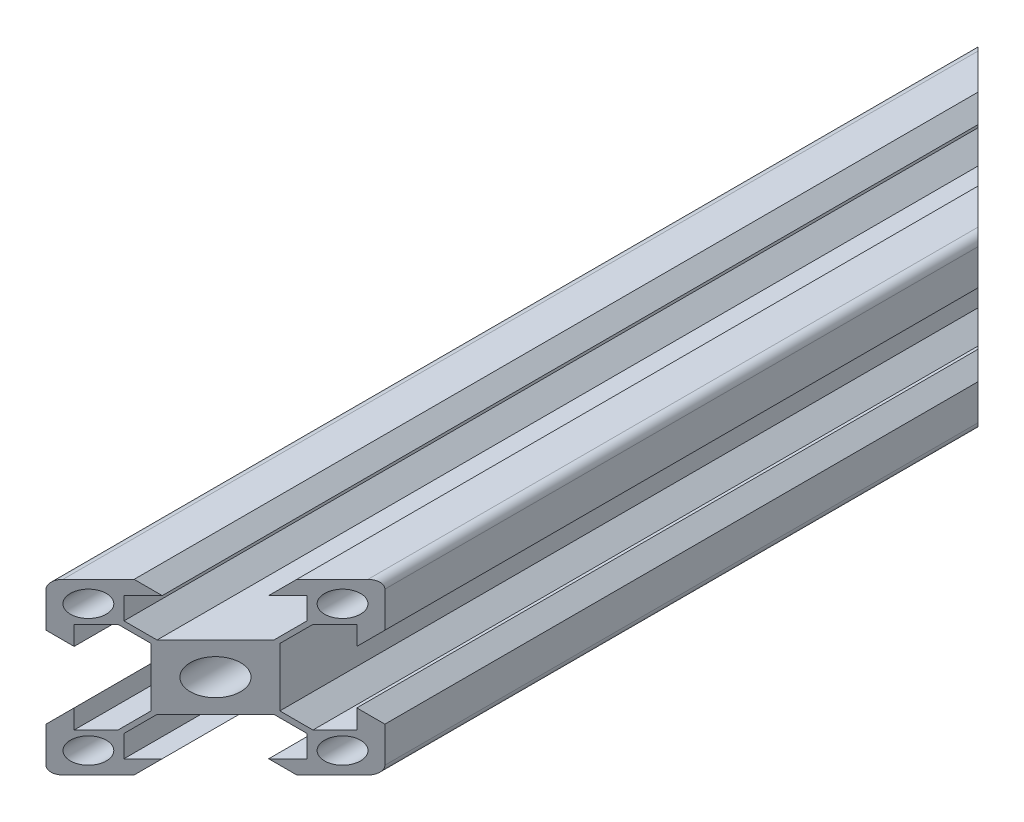
SolidWorks part; units mm, degrees
material "铝管"
ref_plane "前视基准面" through (0, 0, 0) normal (0, 0, 1) x (1, 0, 0)
ref_plane "上视基准面" through (0, 0, 0) normal (0, 1, 0) x (1, 0, 0)
ref_plane "右视基准面" through (0, 0, 0) normal (1, 0, 0) x (0, 0, -1)
sketch "草图1" plane through (0, 0, 0) normal (0, 0, 1) x (1, 0, 0)
  line L0 (0, 0) -> (-40.5659, 40.5659) construction
  line L1 (0, 0) -> (0, 75.5033) construction
  line L2 (-10, 10) -> (-10, 4.8)
  line L3 (-10, 4.8) -> (-8.34, 3.14)
  line L4 (-8.34, 3.14) -> (-8.34, 5.4)
  line L5 (-5.7536, 5.4) -> (-3.8, 3.4464)
  line L6 (-3.8, 3.4464) -> (-3.8, -3.4464)
  line L7 (-3.8, 0) -> (15.6715, 0) construction
  line L8 (-5.4, 8.34) -> (-5.4, 5.7536)
  line L9 (-3.4464, 3.8) -> (3.4464, 3.8)
  line L10 (-5.4, 5.7536) -> (-3.4464, 3.8)
  line L11 (-3.14, 8.34) -> (-5.4, 8.34)
  line L12 (-8.34, 5.4) -> (-5.7536, 5.4)
  line L13 (-4.8, 10) -> (-3.14, 8.34)
  line L14 (-10, 10) -> (-4.8, 10)
  line L15 (-10, -10) -> (-4.8, -10)
  line L16 (-4.8, -10) -> (-3.14, -8.34)
  line L17 (-8.34, -5.4) -> (-5.7536, -5.4)
  line L18 (-3.14, -8.34) -> (-5.4, -8.34)
  line L19 (-5.4, -5.7536) -> (-3.4464, -3.8)
  line L20 (-3.4464, -3.8) -> (3.4464, -3.8)
  line L21 (-5.4, -8.34) -> (-5.4, -5.7536)
  line L22 (-5.7536, -5.4) -> (-3.8, -3.4464)
  line L23 (-8.34, -3.14) -> (-8.34, -5.4)
  line L24 (-10, -4.8) -> (-8.34, -3.14)
  line L25 (-10, -10) -> (-10, -4.8)
  line L26 (10, -10) -> (10, -4.8)
  line L27 (10, -4.8) -> (8.34, -3.14)
  line L28 (8.34, -3.14) -> (8.34, -5.4)
  line L29 (5.7536, -5.4) -> (3.8, -3.4464)
  line L30 (5.4, -8.34) -> (5.4, -5.7536)
  line L31 (5.4, -5.7536) -> (3.4464, -3.8)
  line L32 (3.14, -8.34) -> (5.4, -8.34)
  line L33 (8.34, -5.4) -> (5.7536, -5.4)
  line L34 (4.8, -10) -> (3.14, -8.34)
  line L35 (10, -10) -> (4.8, -10)
  line L36 (10, 10) -> (4.8, 10)
  line L37 (4.8, 10) -> (3.14, 8.34)
  line L38 (8.34, 5.4) -> (5.7536, 5.4)
  line L39 (3.14, 8.34) -> (5.4, 8.34)
  line L40 (5.4, 5.7536) -> (3.4464, 3.8)
  line L41 (5.4, 8.34) -> (5.4, 5.7536)
  line L42 (3.8, 3.4464) -> (3.8, -3.4464)
  line L43 (5.7536, 5.4) -> (3.8, 3.4464)
  line L44 (8.34, 3.14) -> (8.34, 5.4)
  line L45 (10, 4.8) -> (8.34, 3.14)
  line L46 (10, 10) -> (10, 4.8)
  circle A0 centre (-7.5, 7.5) radius 1.5
  circle A1 centre (0, 0) radius 2.1
  circle A2 centre (-7.5, -7.5) radius 1.5
  circle A3 centre (7.5, -7.5) radius 1.5
  circle A4 centre (7.5, 7.5) radius 1.5
  point P54 (0, -3.8)
  point P64 (0, 3.8)
  dimension "D6" = 3
  dimension "D7" = 7.5
  dimension "D9" = 4.2
  dimension "D1" = 45
  dimension "D2" = 4.8
  dimension "D3" = 3.8
  dimension "D4" = 10
  dimension "D5" = 5.4
  dimension "D8" = 3.14
  dimension "D10" = 10
  dimension "D11" = 0.5
extrude "凸台-拉伸1" add sketch "草图1" along normal mid plane 110
fillet "圆角1" radius 1 4 edges at (-10, -10, 0) (10, -10, 0) (-10, 10, 0) (10, 10, 0)
ref_plane "基准面1" through (-32.5, 0, -32.5) normal (0.7071, 0, 0.7071) x (0, -1, 0)
ref_plane "基准面2" through (0, 0, 0) normal (0, 0, -1) x (-1, 0, 0)
sketch "草图2" plane through (-32.5, 0, -32.5) normal (0.7071, 0, 0.7071) x (0, -1, 0)
  line L1 (-18.5745, 31.8198) -> (10.4742, 31.8198)
  line L2 (4.8, 31.8198) -> (9, 31.8198) construction
  line L3 (-18.5745, 31.8198) -> (-18.5745, 65.8351)
  line L4 (-18.5745, 65.8351) -> (10.4742, 65.8351)
  line L5 (10.4742, 65.8351) -> (10.4742, 31.8198)
extrude "切除-拉伸1" cut sketch "草图2" along normal up to next
mirror "镜向1" about plane through (0, 0, 0) normal (0, 0, -1) of "切除-拉伸1"
